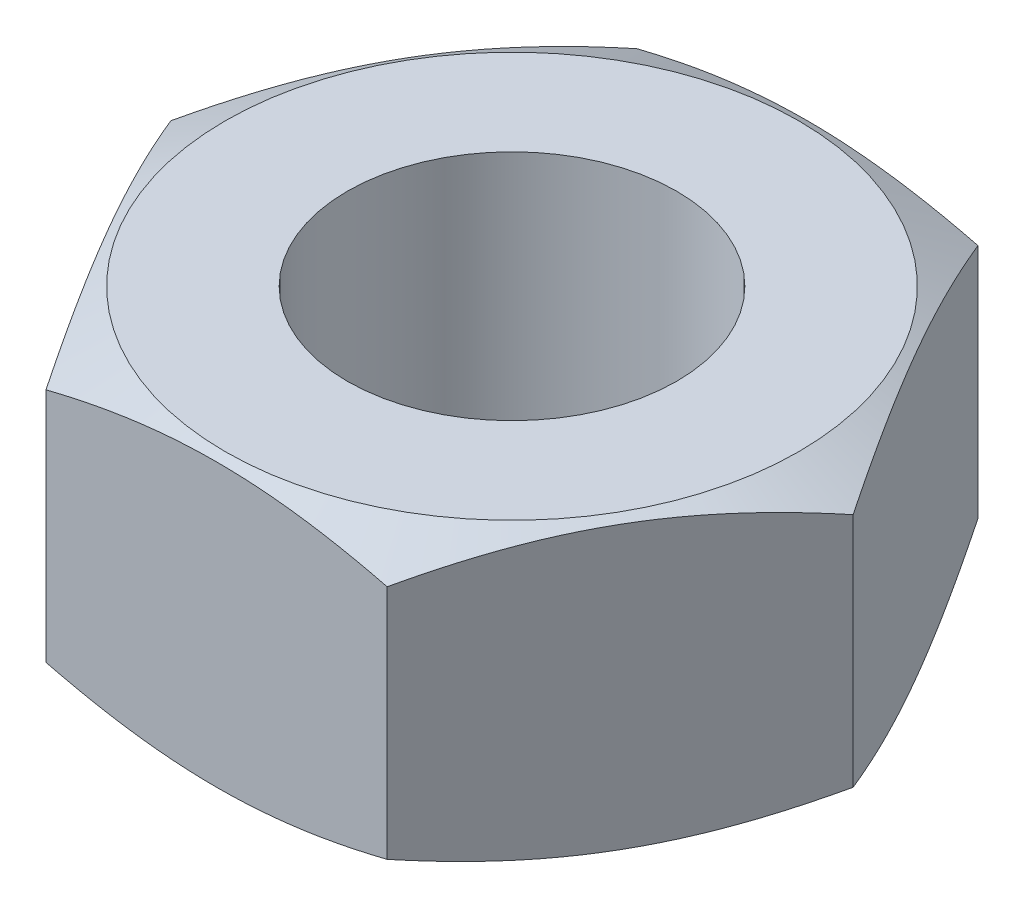
SolidWorks part; units mm, degrees
ref_plane "Alzado" through (0, 0, 0) normal (0, 0, 1) x (1, 0, 0)
ref_plane "Planta" through (0, 0, 0) normal (0, 1, 0) x (1, 0, 0)
ref_plane "Vista lateral" through (0, 0, 0) normal (1, 0, 0) x (0, 0, -1)
sketch "Croquis1" plane through (0, 0, 0) normal (0, 1, 0) x (1, 0, 0)
  line L1 (-6.2618, 0) -> (-3.1309, -5.4229)
  line L2 (-3.1309, -5.4229) -> (3.1309, -5.4229)
  line L3 (3.1309, -5.4229) -> (6.2618, 0)
  line L4 (6.2618, 0) -> (3.1309, 5.4229)
  line L5 (3.1309, 5.4229) -> (-3.1309, 5.4229)
  line L6 (-3.1309, 5.4229) -> (-6.2618, 0)
  circle A0 centre (0, 0) radius 5.4229 construction
  circle A1 centre (0, 0) radius 3.0226
  dimension "D1" = 10.8458
  dimension "D2" = 6.0452
extrude "Saliente-Extruir1" add sketch "Croquis1" along normal blind 5.334
sketch "Croquis2" plane through (0, 0, 0) normal (0, 0, 1) x (1, 0, 0)
  line L0 (-6.2618, 5.334) -> (-6.2618, 0) construction
  line L1 (-6.2618, 5.334) -> (-3.1309, 5.334) construction
  line L2 (-6.2618, 5.334) -> (-6.2618, 4.834)
  line L3 (-6.2618, 5.334) -> (-5.2618, 5.334)
  line L4 (-6.2618, 4.834) -> (-5.2618, 5.334)
  line L5 (0, 0) -> (0, 6.5605) construction
  dimension "D1" = 1
  dimension "D2" = 0.5
revolve "Cortar-Revolución1" cut sketch "Croquis2" angle 360 about L5
sketch "Croquis3" plane through (0, 0, 0) normal (0, 0, 1) x (1, 0, 0)
  line L0 (-6.2618, 0) -> (-5.2618, 0)
  line L1 (-6.2618, 0) -> (-3.1309, 0) construction
  line L2 (-6.2618, 0) -> (-6.2618, 0.5)
  line L3 (-6.2618, 4.834) -> (-6.2618, 0) construction
  line L4 (-5.2618, 0) -> (-6.2618, 0.5)
  dimension "D1" = 0.5
  dimension "D2" = 1
sketch "Croquis4" plane through (0, 0, 0) normal (0, 0, 1) x (1, 0, 0)
  line L0 (0, 0) -> (0, 3.9693) construction
revolve "Cortar-Revolución3" cut sketch "Croquis3" angle 360 about L0
